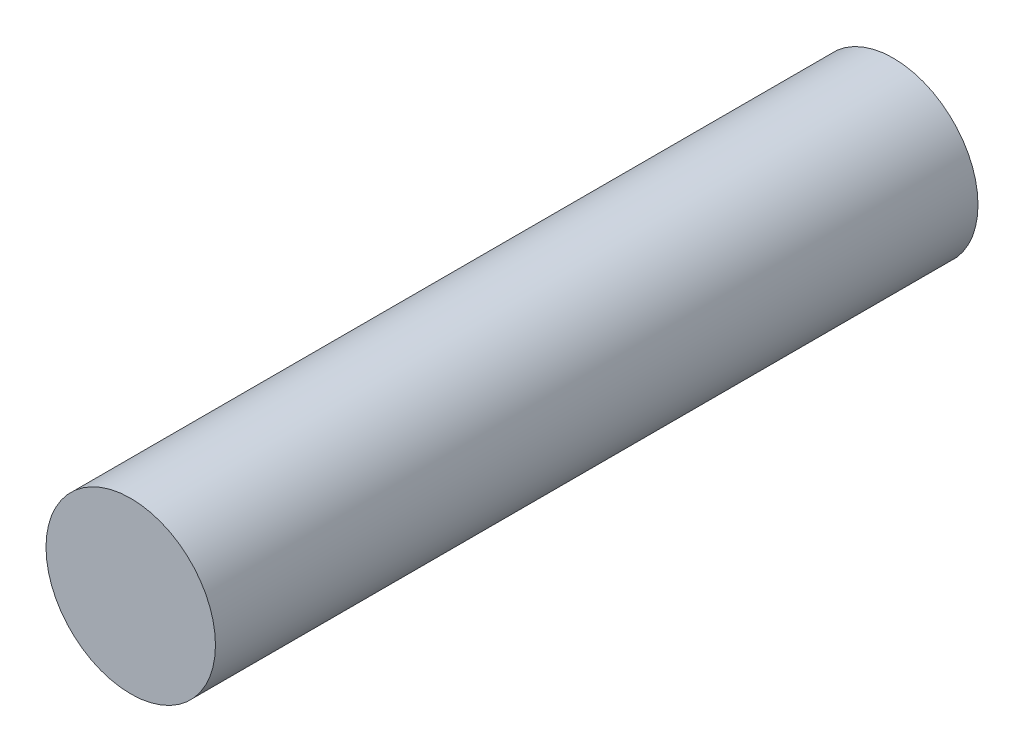
SolidWorks part; units mm, degrees
ref_plane "Front Plane" through (0, 0, 0) normal (0, 0, 1) x (1, 0, 0)
ref_plane "Top Plane" through (0, 0, 0) normal (0, 1, 0) x (1, 0, 0)
ref_plane "Right Plane" through (0, 0, 0) normal (1, 0, 0) x (0, 0, -1)
sketch "Sketch1" plane through (0, 0, 0) normal (0, 0, 1) x (1, 0, 0)
  circle A0 centre (0, 0) radius 12.7
  dimension "D1" = 25.4
extrude "Boss-Extrude1" add sketch "Sketch1" along normal blind 114.3
